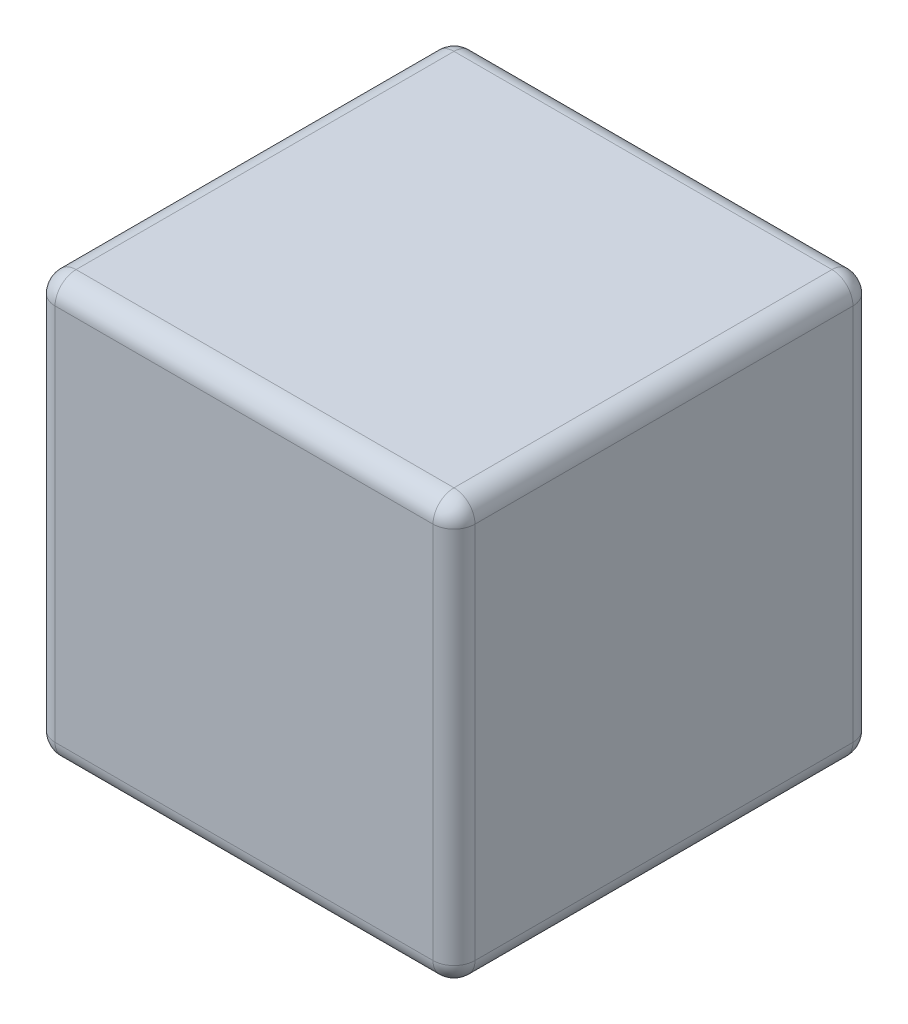
SolidWorks part; units mm, degrees
material "Titanium Ti-13V-11Cr-3Al Solution Treated"
ref_plane "Front Plane" through (0, 0, 0) normal (0, 0, 1) x (1, 0, 0)
ref_plane "Top Plane" through (0, 0, 0) normal (0, 1, 0) x (1, 0, 0)
ref_plane "Right Plane" through (0, 0, 0) normal (1, 0, 0) x (0, 0, -1)
sketch "Sketch1" plane through (0, 0, 0) normal (0, 1, 0) x (1, 0, 0)
  line L1 (0, 0) -> (100, 0)
  line L2 (0, 0) -> (0, 100)
  line L3 (0, 100) -> (100, 100)
  line L4 (100, 0) -> (100, 100)
  dimension "D1" = 100
  dimension "D2" = 100
extrude "Boss-Extrude1" add sketch "Sketch1" along normal blind 100
sketch "Sketch3" plane through (0, 0, -100) normal (0, 0, -1) x (-1, 0, 0)
  line L0 (-100, 100) -> (-100, 0) construction
  line L1 (-100, 100) -> (0, 100) construction
  circle A0 centre (-50, 50) radius 10
  dimension "D1" = 20
  dimension "D2" = 50
  dimension "D3" = 50
extrude "Cut-Extrude1" cut sketch "Sketch3" against normal blind 10
sketch "Sketch4" plane through (0, 0, 0) normal (0, -1, 0) x (1, 0, 0)
  line L0 (0, 0) -> (100, -100) construction
  line L1 (100, -100) -> (0, -100) construction
  line L2 (100, 0) -> (100, -100) construction
  line L3 (0, -100) -> (100, 0) construction
  circle A0 centre (21.7157, -78.2843) radius 10
  circle A1 centre (21.7157, -21.7157) radius 10
  circle A2 centre (78.2843, -78.2843) radius 10
  circle A3 centre (78.2843, -21.7157) radius 10
  circle A4 centre (50, -50) radius 10
  dimension "D1" = 20
  dimension "D2" = 40
  dimension "D3" = 40
  dimension "D4" = 40
  dimension "D5" = 40
extrude "Cut-Extrude2" cut sketch "Sketch4" against normal blind 10
fillet "Fillet5" radius 5 12 edges at (100, 50, -100) (100, 0, -50) (50, 100, -100) (100, 100, -50) (0, 50, -100) (0, 100, -50) (0, 0, -50) (0, 50, 0) (50, 100, 0) (100, 50, 0) (50, 0, 0) (50, 0, -100)
